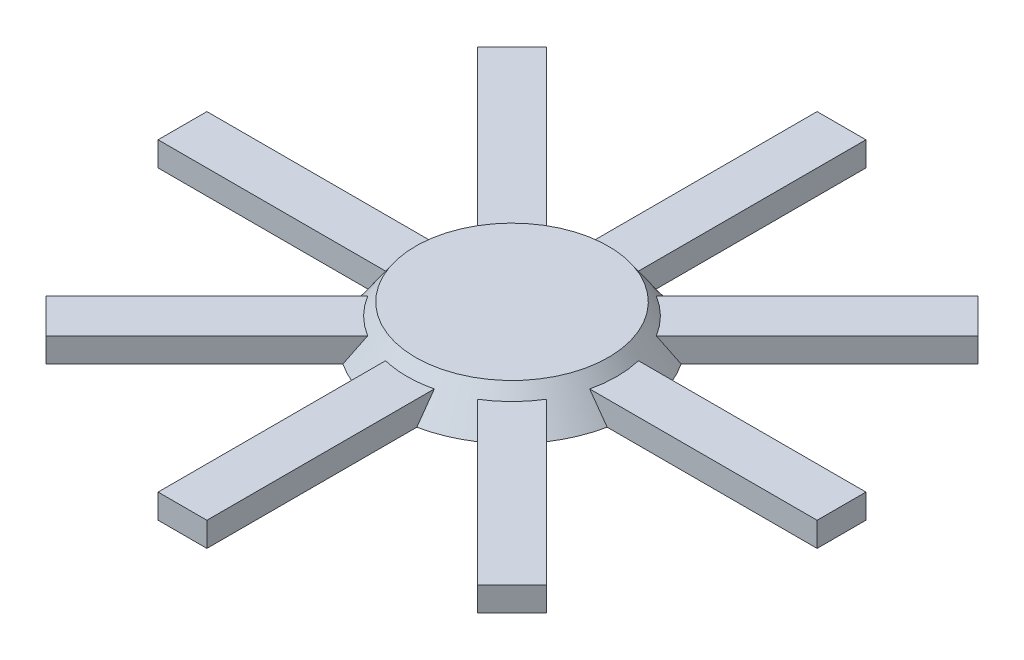
SolidWorks part; units mm, degrees
ref_plane "Спереди" through (0, 0, 0) normal (0, 0, 1) x (1, 0, 0)
ref_plane "Сверху" through (0, 0, 0) normal (0, 1, 0) x (1, 0, 0)
ref_plane "Справа" through (0, 0, 0) normal (1, 0, 0) x (0, 0, -1)
sketch "Эскиз1" plane through (0, 0, 0) normal (0, 1, 0) x (1, 0, 0)
  circle A0 centre (0, 0) radius 10
  dimension "D1" = 20
extrude "Бобышка-Вытянуть1" add sketch "Эскиз1" along normal blind 3 draft 35
sketch "Эскиз2" plane through (0, 0, 0) normal (0, -1, 0) x (1, 0, 0)
  line L1 (-2, 7) -> (2, 7)
  line L2 (-2, 7) -> (-2, 27)
  line L3 (-2, 27) -> (2, 27)
  line L4 (2, 7) -> (2, 27)
  point P4 (0, 7)
  dimension "D1" = 4
  dimension "D2" = 20
  dimension "D3" = 7
extrude "Бобышка-Вытянуть2" add sketch "Эскиз2" against normal blind 2
pattern_circular "Круговой массив1" count 8 over 360 about axis through (0, 0, 0) along (0, 1, 0) of "Бобышка-Вытянуть2"
